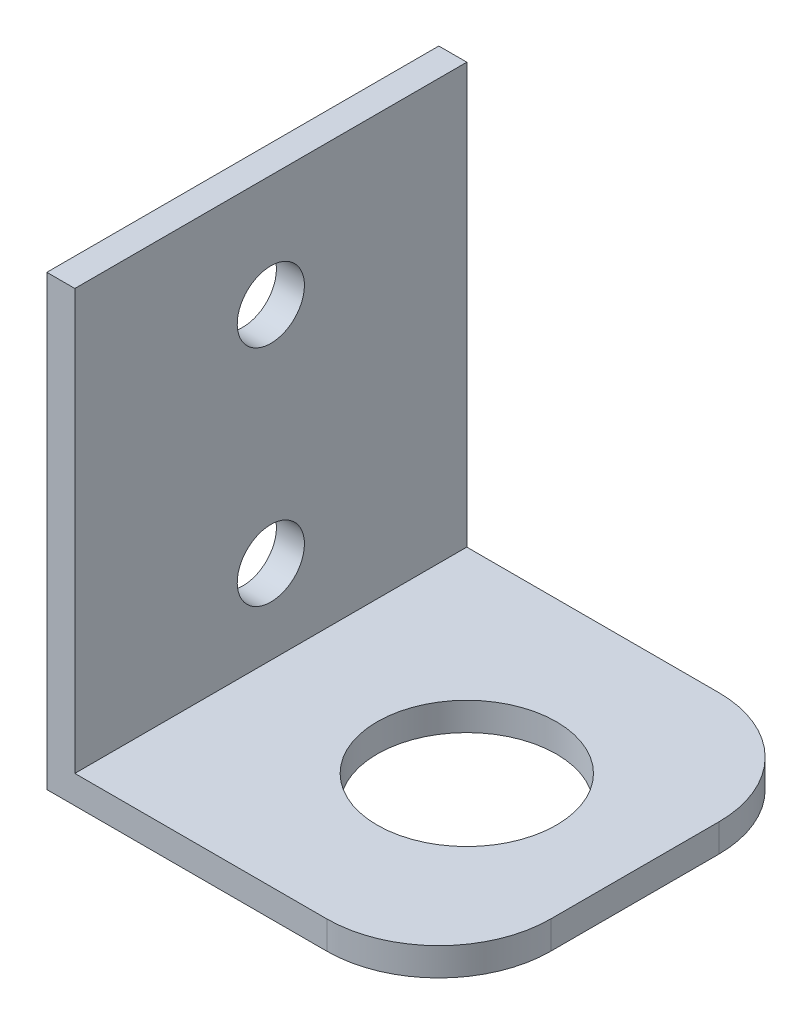
SolidWorks part; units mm, degrees
ref_plane "Plan de face" through (0, 0, 0) normal (0, 0, 1) x (1, 0, 0)
ref_plane "Plan de dessus" through (0, 0, 0) normal (0, 1, 0) x (1, 0, 0)
ref_plane "Plan de droite" through (0, 0, 0) normal (1, 0, 0) x (0, 0, -1)
sketch "Esquisse1" plane through (0, 0, 0) normal (0, 0, 1) x (1, 0, 0)
  line L0 (0, 0) -> (0, -37.5)
  line L1 (0, -37.5) -> (32.5, -37.5)
  line L2 (32.5, -37.5) -> (32.5, -40)
  line L3 (32.5, -40) -> (-2.5, -40)
  line L4 (-2.5, -40) -> (-2.5, 0)
  line L5 (-2.5, 0) -> (0, 0)
  dimension "D1" = 2.5
  dimension "D2" = 2.5
  dimension "D3" = 35
  dimension "D4" = 40
extrude "Boss.-Extru.1" add sketch "Esquisse1" along normal blind 35
sketch "Esquisse2" plane through (0, -40, 0) normal (0, -1, 0) x (-1, 0, 0)
  line L0 (-32.5, -35) -> (-32.5, 0) construction
  circle A0 centre (-17.5, -17.5) radius 8
  dimension "D1" = 15
  dimension "D2" = 16
extrude "Enlèv. mat.-Extru.1" cut sketch "Esquisse2" against normal blind 20
sketch "Esquisse3" plane through (0, 0, 0) normal (1, 0, 0) x (0, 0, -1)
  line L2 (-35, 0) -> (0, 0) construction
  circle A0 centre (-17.5, -10) radius 3
  circle A1 centre (-17.5, -30) radius 3
  dimension "D1" = 6
  dimension "D2" = 20
  dimension "D3" = 10
extrude "Enlèv. mat.-Extru.2" cut sketch "Esquisse3" against normal blind 20
fillet "Congé1" radius 10 2 edges at (32.5, -38.75, 0) (32.5, -38.75, 35)
